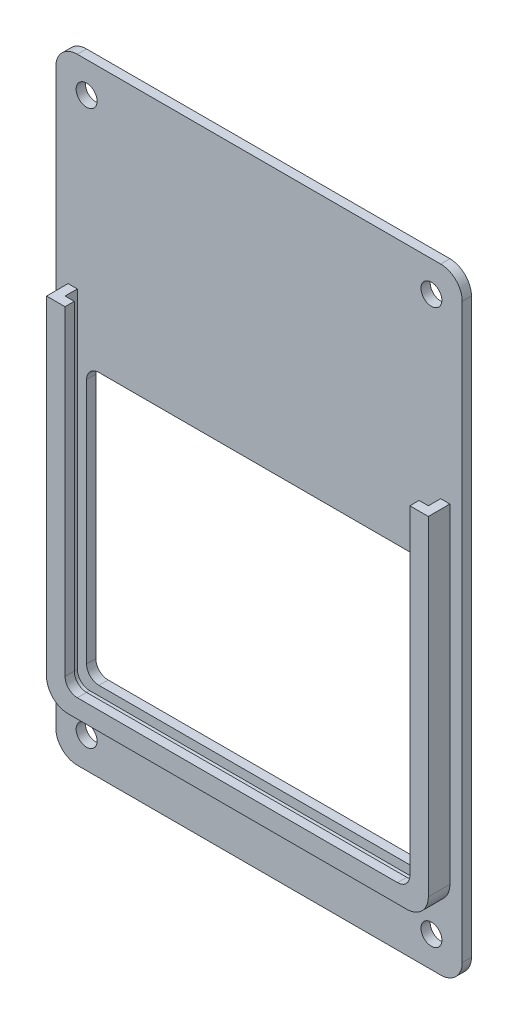
SolidWorks part; units mm, degrees
material "ABS"
ref_plane "Спереди" through (0, 0, 0) normal (0, 0, 1) x (1, 0, 0)
ref_plane "Сверху" through (0, 0, 0) normal (0, 1, 0) x (1, 0, 0)
ref_plane "Справа" through (0, 0, 0) normal (1, 0, 0) x (0, 0, -1)
sketch "Эскиз1" plane through (0, 0, 0) normal (0, 0, 1) x (1, 0, 0)
  line L1 (-33, -50) -> (33, -50)
  line L2 (-33, -50) -> (-33, 50)
  line L3 (-33, 50) -> (33, 50)
  line L4 (33, -50) -> (33, 50)
  line L5 (-33, -50) -> (33, 50) construction
  line L6 (-33, 50) -> (33, -50) construction
  point P0 (0, 0)
  dimension "D1" = 100
  dimension "D2" = 66
extrude "Бобышка-Вытянуть1" add sketch "Эскиз1" along normal blind 1.5 contours L2 L3 L4 L1
fillet "Скругление1" radius 3.5 4 edges at (-33, -50, 0.75) (33, -50, 0.75) (33, 50, 0.75) (-33, 50, 0.75)
sketch "Эскиз2" plane through (0, 0, 1.5) normal (0, 0, 1) x (1, 0, 0)
  line L0 (-29.5, -50) -> (29.5, -50) construction
  line L1 (-33, -50) -> (-24, -50)
  line L2 (-33, -50) -> (-33, -41)
  line L3 (-33, -41) -> (-24, -41)
  line L4 (-24, -50) -> (-24, -41)
  line L5 (33, -50) -> (24, -50)
  line L6 (33, -50) -> (33, -41)
  line L7 (33, -41) -> (24, -41)
  line L8 (24, -50) -> (24, -41)
  line L9 (-28, 7) -> (28, 7)
  line L10 (-28, 7) -> (-28, -37)
  line L11 (-28, -37) -> (28, -37)
  line L12 (28, 7) -> (28, -37)
  line L13 (-33, -46.5) -> (-33, 46.5) construction
  line L14 (33, -46.5) -> (33, 46.5) construction
  dimension "D1" = 57
  dimension "D2" = 5
  dimension "D3" = 5
  dimension "D4" = 13
  dimension "D5" = 9
extrude "Вырез-Вытянуть1" cut sketch "Эскиз2" against normal blind 1.5 contours L12 L9 L10 L3 L4 L11 L8 L7
fillet "Скругление2" radius 2 4 edges at (-28, -37, 0.75) (28, -37, 0.75) (-28, 7, 0.75) (28, 7, 0.75)
sketch "Эскиз3" plane through (0, 0, 1.5) normal (0, 0, 1) x (1, 0, 0)
  line L0 (-26, 7) -> (26, 7) construction
  line L1 (-28, -37) -> (28, -37)
  line L2 (-28, -37) -> (-28, 7)
  line L3 (-28, 7) -> (28, 7)
  line L4 (28, -37) -> (28, 7)
  line L5 (-29.5, -38.5) -> (29.5, -38.5)
  line L6 (-29.5, -38.5) -> (-29.5, 17)
  line L7 (-29.5, 17) -> (29.5, 17)
  line L8 (29.5, -38.5) -> (29.5, 17)
  line L10 (-26, -37) -> (26, -37) construction
  line L11 (28, 5) -> (28, -35) construction
  line L12 (-28, 5) -> (-28, -35) construction
  line L14 (-31, 17) -> (31, 17)
  line L15 (-31, 17) -> (-31, -40)
  line L16 (-31, -40) -> (31, -40)
  line L17 (31, 17) -> (31, -40)
  dimension "D1" = 1.5
  dimension "D2" = 1.5
  dimension "D3" = 1.5
  dimension "D4" = 10
  dimension "D5" = 1.5
  dimension "D6" = 1.5
  dimension "D7" = 1.5
extrude "Бобышка-Вытянуть2" add sketch "Эскиз3" along normal blind 2 contours L17 L14 L8 L5 L6 L15 L16
fillet "Скругление3" radius 2 2 edges at (29.5, -38.5, 2.5) (-29.5, -38.5, 2.5)
sketch "Эскиз4" plane through (0, 0, 3.5) normal (0, 0, 1) x (1, 0, 0)
  line L0 (-28, 5) -> (-28, -35) construction
  line L1 (-31, -40) -> (31, -40)
  line L2 (-31, -40) -> (-31, 17)
  line L3 (-31, 17) -> (31, 17)
  line L4 (31, -40) -> (31, 17)
  line L5 (-28, 17) -> (28, 17)
  line L6 (-28, 17) -> (-28, -37)
  line L7 (-28, -37) -> (28, -37)
  line L8 (28, 17) -> (28, -37)
  line L9 (-26, -37) -> (26, -37) construction
  line L10 (28, 5) -> (28, -35) construction
  line M4 (31, -40) -> (31, 17)
  line M5 (31, 17) -> (29.5, 17)
  line M6 (29.5, 17) -> (29.5, -36.5)
  arc M7 (29.5, -36.5) -> (27.5, -38.5) centre (27.5, -36.5) cw
  line M8 (27.5, -38.5) -> (-27.5, -38.5)
  arc M9 (-27.5, -38.5) -> (-29.5, -36.5) centre (-27.5, -36.5) cw
  line M10 (-29.5, -36.5) -> (-29.5, 17)
  line M11 (-29.5, 17) -> (-31, 17)
  line M12 (-31, 17) -> (-31, -40)
  line M13 (-31, -40) -> (31, -40)
extrude "Бобышка-Вытянуть3" add sketch "Эскиз4" along normal blind 1.5 contours M13 M4 M5 M6 M7 M8 M9 M10 M11 M12 | L3 L8 L7 L6 M10 M9 M8 M7 M6
fillet "Скругление4" radius 2 2 edges at (-28, -37, 4.25) (28, -37, 4.25)
fillet "Скругление5" radius 3.5 2 edges at (-31, -40, 3.25) (31, -40, 3.25)
sketch "Эскиз5" plane through (0, 0, 0) normal (0, 0, -1) x (-1, 0, 0)
  line L1 (-24, -38.5) -> (24, -38.5)
  line L2 (-24, -38.5) -> (-24, -48.5)
  line L3 (-24, -48.5) -> (24, -48.5)
  line L4 (24, -38.5) -> (24, -48.5)
  line L5 (-31.5, 48.5) -> (31.5, 48.5)
  line L6 (-31.5, 48.5) -> (-31.5, 8)
  line L7 (-31.5, 8) -> (31.5, 8)
  line L8 (31.5, 48.5) -> (31.5, 8)
  line L9 (31.5, 48.5) -> (24, 48.5)
  line L10 (31.5, 48.5) -> (31.5, 41)
  line L11 (31.5, 41) -> (24, 41)
  line L12 (24, 48.5) -> (24, 41)
  line L13 (-31.5, 48.5) -> (-24, 48.5)
  line L14 (-31.5, 48.5) -> (-31.5, 41)
  line L15 (-31.5, 41) -> (-24, 41)
  line L16 (-24, 48.5) -> (-24, 41)
  line L18 (-33, -46.5) -> (-33, 46.5) construction
  line L19 (29.5, 50) -> (-29.5, 50) construction
  line L20 (29.5, -50) -> (-29.5, -50) construction
  dimension "D1" = 7.5
  dimension "D2" = 40.5
  dimension "D3" = 63
  dimension "D4" = 1.5
  dimension "D5" = 1.5
  dimension "D6" = 10
  dimension "D7" = 48
  dimension "D8" = 1.5
  dimension "D9" = 9
extrude "Бобышка-Вытянуть4" add sketch "Эскиз5" along normal blind 1.5 contours L5 L16 L15 L6 L7 L8 L11 L12 | L4 L1 L2 L3
fillet "Скругление6" radius 2 12 edges at (24, 41, -0.75) (24, 48.5, -0.75) (31.5, 41, -0.75) (31.5, 8, -0.75) (-31.5, 8, -0.75) (-31.5, 41, -0.75) (-24, 41, -0.75) (-24, 48.5, -0.75) (-24, -48.5, -0.75) (-24, -38.5, -0.75) (24, -38.5, -0.75) (24, -48.5, -0.75)
sketch "Эскиз6" plane through (0, 0, 1.5) normal (0, 0, 1) x (1, 0, 0)
  line L1 (-29.5, 50) -> (29.5, 50) construction
  line L2 (-33, -46.5) -> (-33, 46.5) construction
  line L3 (33, -46.5) -> (33, 46.5) construction
  line L4 (-29.5, -50) -> (29.5, -50) construction
  point P0 (-28, 45)
  point P1 (28, 45)
  point P3 (-28, -45)
  point P4 (28, -45)
  dimension "D1" = 5
  dimension "D2" = 5
  dimension "D3" = 5
  dimension "D4" = 5
hole_wizard "Отверстие с зазором M31" positions "Эскиз7" profile "Эскиз8" hole size "M3" standard "DIN" end condition through all
sketch "Эскиз7" plane through (0, 0, 1.5) normal (0, 0, 1) x (1, 0, 0)
  point P0 (-28, 45)
  point P3 (28, 45)
  point P6 (28, -45)
  point P9 (-28, -45)
sketch "Эскиз8" plane through (-28, 45, 1.5) normal (1, 0, 0) x (0, -1, 0)
  line L0 (0, 0) -> (0, 3)
  line L1 (0, 3) -> (1.7, 3)
  line L2 (1.7, 3) -> (1.7, 0)
  line L5 (1.7, 0) -> (0, 0)
  line L11 (0, -6.35) -> (0, 107.95) construction
  dimension "Диаметр сквозного отверстия" = 3.4
  dimension "Глубина сквозного отверстия" = 3
sketch3d "Трехмерный эскиз1"
  line L0 (-22.5, 43, -1.5) -> (-22.5, 46.5, -1.5)
  line L1 (-22, 47, -1.5) -> (22, 47, -1.5)
  line L2 (22.5, 46.5, -1.5) -> (22.5, 43, -1.5)
  line L3 (26, 39.5, -1.5) -> (29.5, 39.5, -1.5)
  line L4 (30, 39, -1.5) -> (30, 10, -1.5)
  line L5 (29.5, 9.5, -1.5) -> (-29.5, 9.5, -1.5)
  line L6 (-30, 10, -1.5) -> (-30, 39, -1.5)
  line L7 (-29.5, 39.5, -1.5) -> (-26, 39.5, -1.5)
  line L8 (-22.5, 43, -1.5) -> (-22.5, 46.5, -1.5)
  line L9 (-22, 47, -1.5) -> (22, 47, -1.5)
  line L10 (22.5, 46.5, -1.5) -> (22.5, 43, -1.5)
  line L11 (26, 39.5, -1.5) -> (29.5, 39.5, -1.5)
  line L12 (30, 39, -1.5) -> (30, 10, -1.5)
  line L13 (29.5, 9.5, -1.5) -> (-29.5, 9.5, -1.5)
  line L14 (-30, 10, -1.5) -> (-30, 39, -1.5)
  line L15 (-29.5, 39.5, -1.5) -> (-26, 39.5, -1.5)
  spline S0 degree 5 poles (-1959.1652, 518.9756, -1.5) (-791.4073, 54.891, -1.5) (-209.3847, 47.0734, -1.5) (-18.9678, 44.5568, -1.5) (-22.5874, 45.5883, -1.5) (-22.4979, 46.5524, -1.5) (-22.4964, 46.564, -1.5) (-22.4917, 46.5929, -1.5) (-22.4853, 46.6214, -1.5) (-22.4808, 46.6383, -1.5) (-22.4704, 46.6717, -1.5) (-22.457, 46.7041, -1.5) (-22.4496, 46.7199, -1.5) (-22.4333, 46.751, -1.5) (-22.4144, 46.7805, -1.5) (-22.4044, 46.7948, -1.5) (-22.383, 46.8226, -1.5) (-22.3593, 46.8484, -1.5) (-22.3469, 46.8608, -1.5) (-22.321, 46.8844, -1.5) (-22.2931, 46.9056, -1.5) (-22.2788, 46.9156, -1.5) (-22.2492, 46.9344, -1.5) (-22.218, 46.9505, -1.5) (-22.2021, 46.9579, -1.5) (-22.1699, 46.9711, -1.5) (-22.1366, 46.9813, -1.5) (-22.1198, 46.9857, -1.5) (-22.0915, 46.9919, -1.5) (-22.0629, 46.9965, -1.5) (-22.0514, 46.998, -1.5) (-21.0953, 47.085, -1.5) (-20.0736, 43.5304, -1.5) (-22.5419, 233.6284, -1.5) (-34.0122, 814.5009, -1.5) (432.7664, 1987.0289, -1.5) knots -6.044252 -6.044252 -6.044252 -6.044252 -6.044252 -6.044252 0.037136 0.037136 0.037136 0.111408 0.111408 0.111408 0.222815 0.222815 0.222815 0.334223 0.334223 0.334223 0.445631 0.445631 0.445631 0.557039 0.557039 0.557039 0.668446 0.668446 0.668446 0.779854 0.779854 0.779854 0.890372 0.890372 0.890372 0.963754 0.963754 0.963754 6.995146 6.995146 6.995146 6.995146 6.995146 6.995146 only from (-22.5, 46.5, -1.5) to (-22, 47, -1.5)
  spline S1 degree 5 poles (494.4847, 1983.6668, -1.5) (30.3909, 815.9073, -1.5) (22.5734, 233.8847, -1.5) (20.0568, 43.4678, -1.5) (21.0883, 47.0874, -1.5) (22.0524, 46.9979, -1.5) (22.064, 46.9964, -1.5) (22.0929, 46.9917, -1.5) (22.1214, 46.9853, -1.5) (22.1383, 46.9808, -1.5) (22.1717, 46.9704, -1.5) (22.2041, 46.957, -1.5) (22.2199, 46.9496, -1.5) (22.251, 46.9333, -1.5) (22.2805, 46.9144, -1.5) (22.2948, 46.9044, -1.5) (22.3226, 46.883, -1.5) (22.3484, 46.8593, -1.5) (22.3608, 46.8469, -1.5) (22.3844, 46.821, -1.5) (22.4056, 46.7931, -1.5) (22.4156, 46.7788, -1.5) (22.4344, 46.7492, -1.5) (22.4505, 46.718, -1.5) (22.4579, 46.7021, -1.5) (22.4711, 46.6699, -1.5) (22.4813, 46.6366, -1.5) (22.4857, 46.6198, -1.5) (22.4919, 46.5915, -1.5) (22.4965, 46.5629, -1.5) (22.498, 46.5514, -1.5) (22.585, 45.5953, -1.5) (19.0304, 44.5736, -1.5) (209.1284, 47.0419, -1.5) (790.0009, 58.5122, -1.5) (1962.5397, -408.252, -1.4999) knots -6.044252 -6.044252 -6.044252 -6.044252 -6.044252 -6.044252 0.037136 0.037136 0.037136 0.111408 0.111408 0.111408 0.222815 0.222815 0.222815 0.334223 0.334223 0.334223 0.445631 0.445631 0.445631 0.557039 0.557039 0.557039 0.668446 0.668446 0.668446 0.779854 0.779854 0.779854 0.890372 0.890372 0.890372 0.963754 0.963754 0.963754 6.995146 6.995146 6.995146 6.995146 6.995146 6.995146 only from (22, 47, -1.5) to (22.5, 46.5, -1.5)
  spline S2 degree 5 poles (-1977.3234, 23.7298, -1.5) (-763.4699, 42.68, -1.5) (-163.6031, 50.047, -1.5) (29.3183, 50.0118, -1.5) (22.1783, 46.2545, -1.5) (22.5145, 42.6332, -1.5) (22.5252, 42.552, -1.5) (22.5582, 42.3497, -1.5) (22.6028, 42.1502, -1.5) (22.6342, 42.0318, -1.5) (22.7069, 41.798, -1.5) (22.8009, 41.5716, -1.5) (22.853, 41.4605, -1.5) (22.9668, 41.2431, -1.5) (23.0989, 41.0364, -1.5) (23.1694, 40.9361, -1.5) (23.3189, 40.7418, -1.5) (23.485, 40.5613, -1.5) (23.5719, 40.4747, -1.5) (23.7531, 40.3095, -1.5) (23.948, 40.1607, -1.5) (24.0487, 40.0907, -1.5) (24.2558, 39.9594, -1.5) (24.4737, 39.8465, -1.5) (24.585, 39.7949, -1.5) (24.811, 39.7022, -1.5) (25.0441, 39.6307, -1.5) (25.1617, 39.6001, -1.5) (25.3594, 39.5565, -1.5) (25.5598, 39.5243, -1.5) (25.6401, 39.514, -1.5) (29.2335, 39.1869, -1.5) (32.9591, 46.2077, -1.5) (33.0043, -146.8371, -1.5) (25.7256, -746.7213, -1.5) (7.8554, -1960.3791, -1.5) knots -3.19175 -3.19175 -3.19175 -3.19175 -3.19175 -3.19175 0.037136 0.037136 0.037136 0.111408 0.111408 0.111408 0.222815 0.222815 0.222815 0.334223 0.334223 0.334223 0.445631 0.445631 0.445631 0.557039 0.557039 0.557039 0.668446 0.668446 0.668446 0.779854 0.779854 0.779854 0.890372 0.890372 0.890372 0.963754 0.963754 0.963754 4.167936 4.167936 4.167936 4.167936 4.167936 4.167936 only from (22.5, 43, -1.5) to (26, 39.5, -1.5)
  spline S3 degree 5 poles (501.984, 1976.1663, -1.5) (37.8909, 808.4073, -1.5) (30.0734, 226.3847, -1.5) (27.5568, 35.9678, -1.5) (28.5883, 39.5874, -1.5) (29.5524, 39.4979, -1.5) (29.564, 39.4964, -1.5) (29.5929, 39.4917, -1.5) (29.6214, 39.4853, -1.5) (29.6383, 39.4808, -1.5) (29.6717, 39.4704, -1.5) (29.7041, 39.457, -1.5) (29.7199, 39.4496, -1.5) (29.751, 39.4333, -1.5) (29.7805, 39.4144, -1.5) (29.7948, 39.4044, -1.5) (29.8226, 39.383, -1.5) (29.8484, 39.3593, -1.5) (29.8608, 39.3469, -1.5) (29.8844, 39.321, -1.5) (29.9056, 39.2931, -1.5) (29.9156, 39.2788, -1.5) (29.9344, 39.2492, -1.5) (29.9505, 39.218, -1.5) (29.9579, 39.2021, -1.5) (29.9711, 39.1699, -1.5) (29.9813, 39.1366, -1.5) (29.9857, 39.1198, -1.5) (29.9919, 39.0915, -1.5) (29.9965, 39.0629, -1.5) (29.998, 39.0514, -1.5) (30.085, 38.0953, -1.5) (26.5304, 37.0736, -1.5) (216.6284, 39.5419, -1.5) (797.5009, 51.0122, -1.5) (1970.0403, -415.7606, -1.5) knots -6.044252 -6.044252 -6.044252 -6.044252 -6.044252 -6.044252 0.037136 0.037136 0.037136 0.111408 0.111408 0.111408 0.222815 0.222815 0.222815 0.334223 0.334223 0.334223 0.445631 0.445631 0.445631 0.557039 0.557039 0.557039 0.668446 0.668446 0.668446 0.779854 0.779854 0.779854 0.890372 0.890372 0.890372 0.963754 0.963754 0.963754 6.995146 6.995146 6.995146 6.995146 6.995146 6.995146 only from (29.5, 39.5, -1.5) to (30, 39, -1.5)
  spline S4 degree 5 poles (1966.6644, -462.4869, -1.5) (798.9073, 1.6091, -1.5) (216.8847, 9.4266, -1.5) (26.4678, 11.9432, -1.5) (30.0874, 10.9117, -1.5) (29.9979, 9.9476, -1.5) (29.9964, 9.936, -1.5) (29.9917, 9.9071, -1.5) (29.9853, 9.8786, -1.5) (29.9808, 9.8617, -1.5) (29.9704, 9.8283, -1.5) (29.957, 9.7959, -1.5) (29.9496, 9.7801, -1.5) (29.9333, 9.749, -1.5) (29.9144, 9.7195, -1.5) (29.9044, 9.7052, -1.5) (29.883, 9.6774, -1.5) (29.8593, 9.6516, -1.5) (29.8469, 9.6392, -1.5) (29.821, 9.6156, -1.5) (29.7931, 9.5944, -1.5) (29.7788, 9.5844, -1.5) (29.7492, 9.5656, -1.5) (29.718, 9.5495, -1.5) (29.7021, 9.5421, -1.5) (29.6699, 9.5289, -1.5) (29.6366, 9.5187, -1.5) (29.6198, 9.5143, -1.5) (29.5915, 9.5081, -1.5) (29.5629, 9.5035, -1.5) (29.5514, 9.502, -1.5) (28.5953, 9.415, -1.5) (27.5736, 12.9696, -1.5) (30.0419, -177.1284, -1.5) (41.5122, -758.0009, -1.5) (-425.2662, -1930.5375, -1.5) knots -6.044252 -6.044252 -6.044252 -6.044252 -6.044252 -6.044252 0.037136 0.037136 0.037136 0.111408 0.111408 0.111408 0.222815 0.222815 0.222815 0.334223 0.334223 0.334223 0.445631 0.445631 0.445631 0.557039 0.557039 0.557039 0.668446 0.668446 0.668446 0.779854 0.779854 0.779854 0.890372 0.890372 0.890372 0.963754 0.963754 0.963754 6.995146 6.995146 6.995146 6.995146 6.995146 6.995146 only from (30, 10, -1.5) to (29.5, 9.5, -1.5)
  spline S5 degree 5 poles (-501.9891, -1927.1637, -1.5) (-37.8909, -759.4073, -1.5) (-30.0734, -177.3847, -1.5) (-27.5568, 13.0322, -1.5) (-28.5883, 9.4126, -1.5) (-29.5524, 9.5021, -1.5) (-29.564, 9.5036, -1.5) (-29.5929, 9.5083, -1.5) (-29.6214, 9.5147, -1.5) (-29.6383, 9.5192, -1.5) (-29.6717, 9.5296, -1.5) (-29.7041, 9.543, -1.5) (-29.7199, 9.5504, -1.5) (-29.751, 9.5667, -1.5) (-29.7805, 9.5856, -1.5) (-29.7948, 9.5956, -1.5) (-29.8226, 9.617, -1.5) (-29.8484, 9.6407, -1.5) (-29.8608, 9.6531, -1.5) (-29.8844, 9.679, -1.5) (-29.9056, 9.7069, -1.5) (-29.9156, 9.7212, -1.5) (-29.9344, 9.7508, -1.5) (-29.9505, 9.782, -1.5) (-29.9579, 9.7979, -1.5) (-29.9711, 9.8301, -1.5) (-29.9813, 9.8634, -1.5) (-29.9857, 9.8802, -1.5) (-29.9919, 9.9085, -1.5) (-29.9965, 9.9371, -1.5) (-29.998, 9.9486, -1.5) (-30.085, 10.9047, -1.5) (-26.5304, 11.9264, -1.5) (-216.6284, 9.4581, -1.5) (-797.5009, -2.0123, -1.5) (-1970.043, 464.7742, -1.5) knots -6.044252 -6.044252 -6.044252 -6.044252 -6.044252 -6.044252 0.037136 0.037136 0.037136 0.111408 0.111408 0.111408 0.222815 0.222815 0.222815 0.334223 0.334223 0.334223 0.445631 0.445631 0.445631 0.557039 0.557039 0.557039 0.668446 0.668446 0.668446 0.779854 0.779854 0.779854 0.890372 0.890372 0.890372 0.963754 0.963754 0.963754 6.995146 6.995146 6.995146 6.995146 6.995146 6.995146 only from (-29.5, 9.5, -1.5) to (-30, 10, -1.5)
  spline S6 degree 5 poles (-1966.6635, 511.5027, -1.5) (-798.9073, 47.3909, -1.5) (-216.8847, 39.5734, -1.5) (-26.4678, 37.0568, -1.5) (-30.0874, 38.0883, -1.5) (-29.9979, 39.0524, -1.5) (-29.9964, 39.064, -1.5) (-29.9917, 39.0929, -1.5) (-29.9853, 39.1214, -1.5) (-29.9808, 39.1383, -1.5) (-29.9704, 39.1717, -1.5) (-29.957, 39.2041, -1.5) (-29.9496, 39.2199, -1.5) (-29.9333, 39.251, -1.5) (-29.9144, 39.2805, -1.5) (-29.9044, 39.2948, -1.5) (-29.883, 39.3226, -1.5) (-29.8593, 39.3484, -1.5) (-29.8469, 39.3608, -1.5) (-29.821, 39.3844, -1.5) (-29.7931, 39.4056, -1.5) (-29.7788, 39.4156, -1.5) (-29.7492, 39.4344, -1.5) (-29.718, 39.4505, -1.5) (-29.7021, 39.4579, -1.5) (-29.6699, 39.4711, -1.5) (-29.6366, 39.4813, -1.5) (-29.6198, 39.4857, -1.5) (-29.5915, 39.4919, -1.5) (-29.5629, 39.4965, -1.5) (-29.5514, 39.498, -1.5) (-28.5953, 39.585, -1.5) (-27.5736, 36.0304, -1.5) (-30.0419, 226.1284, -1.5) (-41.5122, 807.0009, -1.5) (425.2707, 1979.5276, -1.5) knots -6.044252 -6.044252 -6.044252 -6.044252 -6.044252 -6.044252 0.037136 0.037136 0.037136 0.111408 0.111408 0.111408 0.222815 0.222815 0.222815 0.334223 0.334223 0.334223 0.445631 0.445631 0.445631 0.557039 0.557039 0.557039 0.668446 0.668446 0.668446 0.779854 0.779854 0.779854 0.890372 0.890372 0.890372 0.963754 0.963754 0.963754 6.995146 6.995146 6.995146 6.995146 6.995146 6.995146 only from (-30, 39, -1.5) to (-29.5, 39.5, -1.5)
  spline S7 degree 5 poles (-6.7304, -1960.3231, -1.5) (-25.68, -746.4699, -1.5) (-33.047, -146.6031, -1.5) (-33.0118, 46.3183, -1.5) (-29.2545, 39.1783, -1.5) (-25.6332, 39.5145, -1.5) (-25.552, 39.5252, -1.5) (-25.3497, 39.5582, -1.5) (-25.1502, 39.6028, -1.5) (-25.0318, 39.6342, -1.5) (-24.798, 39.7069, -1.5) (-24.5716, 39.8009, -1.5) (-24.4605, 39.853, -1.5) (-24.2431, 39.9668, -1.5) (-24.0364, 40.0989, -1.5) (-23.9361, 40.1694, -1.5) (-23.7418, 40.3189, -1.5) (-23.5613, 40.485, -1.5) (-23.4747, 40.5719, -1.5) (-23.3095, 40.7531, -1.5) (-23.1607, 40.948, -1.5) (-23.0907, 41.0487, -1.5) (-22.9594, 41.2558, -1.5) (-22.8465, 41.4737, -1.5) (-22.7949, 41.585, -1.5) (-22.7022, 41.811, -1.5) (-22.6307, 42.0441, -1.5) (-22.6001, 42.1617, -1.5) (-22.5565, 42.3594, -1.5) (-22.5243, 42.5598, -1.5) (-22.514, 42.6401, -1.5) (-22.1869, 46.2335, -1.5) (-29.2077, 49.9591, -1.5) (163.8371, 50.0043, -1.5) (763.7213, 42.7256, -1.5) (1977.3792, 24.8548, -1.5) knots -3.19175 -3.19175 -3.19175 -3.19175 -3.19175 -3.19175 0.037136 0.037136 0.037136 0.111408 0.111408 0.111408 0.222815 0.222815 0.222815 0.334223 0.334223 0.334223 0.445631 0.445631 0.445631 0.557039 0.557039 0.557039 0.668446 0.668446 0.668446 0.779854 0.779854 0.779854 0.890372 0.890372 0.890372 0.963754 0.963754 0.963754 4.167936 4.167936 4.167936 4.167936 4.167936 4.167936 only from (-26, 39.5, -1.5) to (-22.5, 43, -1.5)
  spline S8 degree 5 poles (-22.5, 46.5, -1.5) (-22.5, 46.5058, -1.5) (-22.5, 46.5117, -1.5) (-22.5, 46.5175, -1.5) (-22.4996, 46.5349, -1.5) (-22.4979, 46.5524, -1.5) (-22.4964, 46.564, -1.5) (-22.4917, 46.5929, -1.5) (-22.4853, 46.6214, -1.5) (-22.4808, 46.6383, -1.5) (-22.4704, 46.6717, -1.5) (-22.457, 46.7041, -1.5) (-22.4496, 46.7199, -1.5) (-22.4333, 46.751, -1.5) (-22.4144, 46.7805, -1.5) (-22.4044, 46.7948, -1.5) (-22.383, 46.8226, -1.5) (-22.3593, 46.8484, -1.5) (-22.3469, 46.8608, -1.5) (-22.321, 46.8844, -1.5) (-22.2931, 46.9056, -1.5) (-22.2788, 46.9156, -1.5) (-22.2492, 46.9344, -1.5) (-22.218, 46.9505, -1.5) (-22.2021, 46.9579, -1.5) (-22.1699, 46.9711, -1.5) (-22.1366, 46.9813, -1.5) (-22.1198, 46.9857, -1.5) (-22.0915, 46.9919, -1.5) (-22.0629, 46.9965, -1.5) (-22.0514, 46.998, -1.5) (-22.0342, 46.9996, -1.5) (-22.0171, 47, -1.5) (-22.0114, 47, -1.5) (-22.0057, 47, -1.5) (-22, 47, -1.5) knots 0 0 0 0 0 0 0.037136 0.037136 0.037136 0.111408 0.111408 0.111408 0.222815 0.222815 0.222815 0.334223 0.334223 0.334223 0.445631 0.445631 0.445631 0.557039 0.557039 0.557039 0.668446 0.668446 0.668446 0.779854 0.779854 0.779854 0.890372 0.890372 0.890372 0.963754 0.963754 0.963754 1 1 1 1 1 1
  spline S9 degree 5 poles (22, 47, -1.5) (22.0058, 47, -1.5) (22.0117, 47, -1.5) (22.0175, 47, -1.5) (22.0349, 46.9996, -1.5) (22.0524, 46.9979, -1.5) (22.064, 46.9964, -1.5) (22.0929, 46.9917, -1.5) (22.1214, 46.9853, -1.5) (22.1383, 46.9808, -1.5) (22.1717, 46.9704, -1.5) (22.2041, 46.957, -1.5) (22.2199, 46.9496, -1.5) (22.251, 46.9333, -1.5) (22.2805, 46.9144, -1.5) (22.2948, 46.9044, -1.5) (22.3226, 46.883, -1.5) (22.3484, 46.8593, -1.5) (22.3608, 46.8469, -1.5) (22.3844, 46.821, -1.5) (22.4056, 46.7931, -1.5) (22.4156, 46.7788, -1.5) (22.4344, 46.7492, -1.5) (22.4505, 46.718, -1.5) (22.4579, 46.7021, -1.5) (22.4711, 46.6699, -1.5) (22.4813, 46.6366, -1.5) (22.4857, 46.6198, -1.5) (22.4919, 46.5915, -1.5) (22.4965, 46.5629, -1.5) (22.498, 46.5514, -1.5) (22.4996, 46.5342, -1.5) (22.5, 46.5171, -1.5) (22.5, 46.5114, -1.5) (22.5, 46.5057, -1.5) (22.5, 46.5, -1.5) knots 0 0 0 0 0 0 0.037136 0.037136 0.037136 0.111408 0.111408 0.111408 0.222815 0.222815 0.222815 0.334223 0.334223 0.334223 0.445631 0.445631 0.445631 0.557039 0.557039 0.557039 0.668446 0.668446 0.668446 0.779854 0.779854 0.779854 0.890372 0.890372 0.890372 0.963754 0.963754 0.963754 1 1 1 1 1 1
  spline S10 degree 5 poles (22.5, 43, -1.5) (22.5, 42.9592, -1.5) (22.5, 42.9184, -1.5) (22.5003, 42.8777, -1.5) (22.5031, 42.7554, -1.5) (22.5145, 42.6332, -1.5) (22.5252, 42.552, -1.5) (22.5582, 42.3497, -1.5) (22.6028, 42.1502, -1.5) (22.6342, 42.0318, -1.5) (22.7069, 41.798, -1.5) (22.8009, 41.5716, -1.5) (22.853, 41.4605, -1.5) (22.9668, 41.2431, -1.5) (23.0989, 41.0364, -1.5) (23.1694, 40.9361, -1.5) (23.3189, 40.7418, -1.5) (23.485, 40.5613, -1.5) (23.5719, 40.4747, -1.5) (23.7531, 40.3095, -1.5) (23.948, 40.1607, -1.5) (24.0487, 40.0907, -1.5) (24.2558, 39.9594, -1.5) (24.4737, 39.8465, -1.5) (24.585, 39.7949, -1.5) (24.811, 39.7022, -1.5) (25.0441, 39.6307, -1.5) (25.1617, 39.6001, -1.5) (25.3594, 39.5565, -1.5) (25.5598, 39.5243, -1.5) (25.6401, 39.514, -1.5) (25.7603, 39.503, -1.5) (25.8806, 39.5003, -1.5) (25.9204, 39.5, -1.5) (25.9602, 39.5, -1.5) (26, 39.5, -1.5) knots 0 0 0 0 0 0 0.037136 0.037136 0.037136 0.111408 0.111408 0.111408 0.222815 0.222815 0.222815 0.334223 0.334223 0.334223 0.445631 0.445631 0.445631 0.557039 0.557039 0.557039 0.668446 0.668446 0.668446 0.779854 0.779854 0.779854 0.890372 0.890372 0.890372 0.963754 0.963754 0.963754 1 1 1 1 1 1
  spline S11 degree 5 poles (29.5, 39.5, -1.5) (29.5058, 39.5, -1.5) (29.5117, 39.5, -1.5) (29.5175, 39.5, -1.5) (29.5349, 39.4996, -1.5) (29.5524, 39.4979, -1.5) (29.564, 39.4964, -1.5) (29.5929, 39.4917, -1.5) (29.6214, 39.4853, -1.5) (29.6383, 39.4808, -1.5) (29.6717, 39.4704, -1.5) (29.7041, 39.457, -1.5) (29.7199, 39.4496, -1.5) (29.751, 39.4333, -1.5) (29.7805, 39.4144, -1.5) (29.7948, 39.4044, -1.5) (29.8226, 39.383, -1.5) (29.8484, 39.3593, -1.5) (29.8608, 39.3469, -1.5) (29.8844, 39.321, -1.5) (29.9056, 39.2931, -1.5) (29.9156, 39.2788, -1.5) (29.9344, 39.2492, -1.5) (29.9505, 39.218, -1.5) (29.9579, 39.2021, -1.5) (29.9711, 39.1699, -1.5) (29.9813, 39.1366, -1.5) (29.9857, 39.1198, -1.5) (29.9919, 39.0915, -1.5) (29.9965, 39.0629, -1.5) (29.998, 39.0514, -1.5) (29.9996, 39.0342, -1.5) (30, 39.0171, -1.5) (30, 39.0114, -1.5) (30, 39.0057, -1.5) (30, 39, -1.5) knots 0 0 0 0 0 0 0.037136 0.037136 0.037136 0.111408 0.111408 0.111408 0.222815 0.222815 0.222815 0.334223 0.334223 0.334223 0.445631 0.445631 0.445631 0.557039 0.557039 0.557039 0.668446 0.668446 0.668446 0.779854 0.779854 0.779854 0.890372 0.890372 0.890372 0.963754 0.963754 0.963754 1 1 1 1 1 1
  spline S12 degree 5 poles (30, 10, -1.5) (30, 9.9942, -1.5) (30, 9.9883, -1.5) (30, 9.9825, -1.5) (29.9996, 9.9651, -1.5) (29.9979, 9.9476, -1.5) (29.9964, 9.936, -1.5) (29.9917, 9.9071, -1.5) (29.9853, 9.8786, -1.5) (29.9808, 9.8617, -1.5) (29.9704, 9.8283, -1.5) (29.957, 9.7959, -1.5) (29.9496, 9.7801, -1.5) (29.9333, 9.749, -1.5) (29.9144, 9.7195, -1.5) (29.9044, 9.7052, -1.5) (29.883, 9.6774, -1.5) (29.8593, 9.6516, -1.5) (29.8469, 9.6392, -1.5) (29.821, 9.6156, -1.5) (29.7931, 9.5944, -1.5) (29.7788, 9.5844, -1.5) (29.7492, 9.5656, -1.5) (29.718, 9.5495, -1.5) (29.7021, 9.5421, -1.5) (29.6699, 9.5289, -1.5) (29.6366, 9.5187, -1.5) (29.6198, 9.5143, -1.5) (29.5915, 9.5081, -1.5) (29.5629, 9.5035, -1.5) (29.5514, 9.502, -1.5) (29.5342, 9.5004, -1.5) (29.5171, 9.5, -1.5) (29.5114, 9.5, -1.5) (29.5057, 9.5, -1.5) (29.5, 9.5, -1.5) knots 0 0 0 0 0 0 0.037136 0.037136 0.037136 0.111408 0.111408 0.111408 0.222815 0.222815 0.222815 0.334223 0.334223 0.334223 0.445631 0.445631 0.445631 0.557039 0.557039 0.557039 0.668446 0.668446 0.668446 0.779854 0.779854 0.779854 0.890372 0.890372 0.890372 0.963754 0.963754 0.963754 1 1 1 1 1 1
  spline S13 degree 5 poles (-29.5, 9.5, -1.5) (-29.5058, 9.5, -1.5) (-29.5117, 9.5, -1.5) (-29.5175, 9.5, -1.5) (-29.5349, 9.5004, -1.5) (-29.5524, 9.5021, -1.5) (-29.564, 9.5036, -1.5) (-29.5929, 9.5083, -1.5) (-29.6214, 9.5147, -1.5) (-29.6383, 9.5192, -1.5) (-29.6717, 9.5296, -1.5) (-29.7041, 9.543, -1.5) (-29.7199, 9.5504, -1.5) (-29.751, 9.5667, -1.5) (-29.7805, 9.5856, -1.5) (-29.7948, 9.5956, -1.5) (-29.8226, 9.617, -1.5) (-29.8484, 9.6407, -1.5) (-29.8608, 9.6531, -1.5) (-29.8844, 9.679, -1.5) (-29.9056, 9.7069, -1.5) (-29.9156, 9.7212, -1.5) (-29.9344, 9.7508, -1.5) (-29.9505, 9.782, -1.5) (-29.9579, 9.7979, -1.5) (-29.9711, 9.8301, -1.5) (-29.9813, 9.8634, -1.5) (-29.9857, 9.8802, -1.5) (-29.9919, 9.9085, -1.5) (-29.9965, 9.9371, -1.5) (-29.998, 9.9486, -1.5) (-29.9996, 9.9658, -1.5) (-30, 9.9829, -1.5) (-30, 9.9886, -1.5) (-30, 9.9943, -1.5) (-30, 10, -1.5) knots 0 0 0 0 0 0 0.037136 0.037136 0.037136 0.111408 0.111408 0.111408 0.222815 0.222815 0.222815 0.334223 0.334223 0.334223 0.445631 0.445631 0.445631 0.557039 0.557039 0.557039 0.668446 0.668446 0.668446 0.779854 0.779854 0.779854 0.890372 0.890372 0.890372 0.963754 0.963754 0.963754 1 1 1 1 1 1
  spline S14 degree 5 poles (-30, 39, -1.5) (-30, 39.0058, -1.5) (-30, 39.0117, -1.5) (-30, 39.0175, -1.5) (-29.9996, 39.0349, -1.5) (-29.9979, 39.0524, -1.5) (-29.9964, 39.064, -1.5) (-29.9917, 39.0929, -1.5) (-29.9853, 39.1214, -1.5) (-29.9808, 39.1383, -1.5) (-29.9704, 39.1717, -1.5) (-29.957, 39.2041, -1.5) (-29.9496, 39.2199, -1.5) (-29.9333, 39.251, -1.5) (-29.9144, 39.2805, -1.5) (-29.9044, 39.2948, -1.5) (-29.883, 39.3226, -1.5) (-29.8593, 39.3484, -1.5) (-29.8469, 39.3608, -1.5) (-29.821, 39.3844, -1.5) (-29.7931, 39.4056, -1.5) (-29.7788, 39.4156, -1.5) (-29.7492, 39.4344, -1.5) (-29.718, 39.4505, -1.5) (-29.7021, 39.4579, -1.5) (-29.6699, 39.4711, -1.5) (-29.6366, 39.4813, -1.5) (-29.6198, 39.4857, -1.5) (-29.5915, 39.4919, -1.5) (-29.5629, 39.4965, -1.5) (-29.5514, 39.498, -1.5) (-29.5342, 39.4996, -1.5) (-29.5171, 39.5, -1.5) (-29.5114, 39.5, -1.5) (-29.5057, 39.5, -1.5) (-29.5, 39.5, -1.5) knots 0 0 0 0 0 0 0.037136 0.037136 0.037136 0.111408 0.111408 0.111408 0.222815 0.222815 0.222815 0.334223 0.334223 0.334223 0.445631 0.445631 0.445631 0.557039 0.557039 0.557039 0.668446 0.668446 0.668446 0.779854 0.779854 0.779854 0.890372 0.890372 0.890372 0.963754 0.963754 0.963754 1 1 1 1 1 1
  spline S15 degree 5 poles (-26, 39.5, -1.5) (-25.9592, 39.5, -1.5) (-25.9184, 39.5, -1.5) (-25.8777, 39.5003, -1.5) (-25.7554, 39.5031, -1.5) (-25.6332, 39.5145, -1.5) (-25.552, 39.5252, -1.5) (-25.3497, 39.5582, -1.5) (-25.1502, 39.6028, -1.5) (-25.0318, 39.6342, -1.5) (-24.798, 39.7069, -1.5) (-24.5716, 39.8009, -1.5) (-24.4605, 39.853, -1.5) (-24.2431, 39.9668, -1.5) (-24.0364, 40.0989, -1.5) (-23.9361, 40.1694, -1.5) (-23.7418, 40.3189, -1.5) (-23.5613, 40.485, -1.5) (-23.4747, 40.5719, -1.5) (-23.3095, 40.7531, -1.5) (-23.1607, 40.948, -1.5) (-23.0907, 41.0487, -1.5) (-22.9594, 41.2558, -1.5) (-22.8465, 41.4737, -1.5) (-22.7949, 41.585, -1.5) (-22.7022, 41.811, -1.5) (-22.6307, 42.0441, -1.5) (-22.6001, 42.1617, -1.5) (-22.5565, 42.3594, -1.5) (-22.5243, 42.5598, -1.5) (-22.514, 42.6401, -1.5) (-22.503, 42.7603, -1.5) (-22.5003, 42.8806, -1.5) (-22.5, 42.9204, -1.5) (-22.5, 42.9602, -1.5) (-22.5, 43, -1.5) knots 0 0 0 0 0 0 0.037136 0.037136 0.037136 0.111408 0.111408 0.111408 0.222815 0.222815 0.222815 0.334223 0.334223 0.334223 0.445631 0.445631 0.445631 0.557039 0.557039 0.557039 0.668446 0.668446 0.668446 0.779854 0.779854 0.779854 0.890372 0.890372 0.890372 0.963754 0.963754 0.963754 1 1 1 1 1 1
  dimension "D1" = 1.5
extrude "Вырез-Вытянуть2" cut sketch "Трехмерный эскиз1" along direction (0, 0, 1) on the side against the normal up to surface (1.5 mm away)
sketch3d "Трехмерный эскиз2"
  line L0 (22.5, -40.5, -1.5) -> (22.5, -46.5, -1.5)
  line L1 (22, -47, -1.5) -> (-22, -47, -1.5)
  line L2 (-22.5, -46.5, -1.5) -> (-22.5, -40.5, -1.5)
  line L3 (-22, -40, -1.5) -> (22, -40, -1.5)
  line L4 (22.5, -40.5, -1.5) -> (22.5, -46.5, -1.5)
  line L5 (22, -47, -1.5) -> (-22, -47, -1.5)
  line L6 (-22.5, -46.5, -1.5) -> (-22.5, -40.5, -1.5)
  line L7 (-22, -40, -1.5) -> (22, -40, -1.5)
  spline S0 degree 5 poles (1959.1668, -518.9851, -1.5) (791.4073, -54.8909, -1.5) (209.3847, -47.0734, -1.5) (18.9678, -44.5568, -1.5) (22.5874, -45.5883, -1.5) (22.4979, -46.5524, -1.5) (22.4964, -46.564, -1.5) (22.4917, -46.5929, -1.5) (22.4853, -46.6214, -1.5) (22.4808, -46.6383, -1.5) (22.4704, -46.6717, -1.5) (22.457, -46.7041, -1.5) (22.4496, -46.7199, -1.5) (22.4333, -46.751, -1.5) (22.4144, -46.7805, -1.5) (22.4044, -46.7948, -1.5) (22.383, -46.8226, -1.5) (22.3593, -46.8484, -1.5) (22.3469, -46.8608, -1.5) (22.321, -46.8844, -1.5) (22.2931, -46.9056, -1.5) (22.2788, -46.9156, -1.5) (22.2492, -46.9344, -1.5) (22.218, -46.9505, -1.5) (22.2021, -46.9579, -1.5) (22.1699, -46.9711, -1.5) (22.1366, -46.9813, -1.5) (22.1198, -46.9857, -1.5) (22.0915, -46.9919, -1.5) (22.0629, -46.9965, -1.5) (22.0514, -46.998, -1.5) (21.0953, -47.085, -1.5) (20.0736, -43.5304, -1.5) (22.5419, -233.6284, -1.5) (34.0122, -814.5009, -1.5) (-432.7709, -1987.0314, -1.5) knots -6.044252 -6.044252 -6.044252 -6.044252 -6.044252 -6.044252 0.037136 0.037136 0.037136 0.111408 0.111408 0.111408 0.222815 0.222815 0.222815 0.334223 0.334223 0.334223 0.445631 0.445631 0.445631 0.557039 0.557039 0.557039 0.668446 0.668446 0.668446 0.779854 0.779854 0.779854 0.890372 0.890372 0.890372 0.963754 0.963754 0.963754 6.995146 6.995146 6.995146 6.995146 6.995146 6.995146 only from (22.5, -46.5, -1.5) to (22, -47, -1.5)
  spline S1 degree 5 poles (-494.491, -1983.6636, -1.5) (-30.3909, -815.9073, -1.5) (-22.5734, -233.8847, -1.5) (-20.0568, -43.4678, -1.5) (-21.0883, -47.0874, -1.5) (-22.0524, -46.9979, -1.5) (-22.064, -46.9964, -1.5) (-22.0929, -46.9917, -1.5) (-22.1214, -46.9853, -1.5) (-22.1383, -46.9808, -1.5) (-22.1717, -46.9704, -1.5) (-22.2041, -46.957, -1.5) (-22.2199, -46.9496, -1.5) (-22.251, -46.9333, -1.5) (-22.2805, -46.9144, -1.5) (-22.2948, -46.9044, -1.5) (-22.3226, -46.883, -1.5) (-22.3484, -46.8593, -1.5) (-22.3608, -46.8469, -1.5) (-22.3844, -46.821, -1.5) (-22.4056, -46.7931, -1.5) (-22.4156, -46.7788, -1.5) (-22.4344, -46.7492, -1.5) (-22.4505, -46.718, -1.5) (-22.4579, -46.7021, -1.5) (-22.4711, -46.6699, -1.5) (-22.4813, -46.6366, -1.5) (-22.4857, -46.6198, -1.5) (-22.4919, -46.5915, -1.5) (-22.4965, -46.5629, -1.5) (-22.498, -46.5514, -1.5) (-22.585, -45.5953, -1.5) (-19.0304, -44.5736, -1.5) (-209.1284, -47.0419, -1.5) (-790.0009, -58.5123, -1.5) (-1962.541, 408.275, -1.4999) knots -6.044252 -6.044252 -6.044252 -6.044252 -6.044252 -6.044252 0.037136 0.037136 0.037136 0.111408 0.111408 0.111408 0.222815 0.222815 0.222815 0.334223 0.334223 0.334223 0.445631 0.445631 0.445631 0.557039 0.557039 0.557039 0.668446 0.668446 0.668446 0.779854 0.779854 0.779854 0.890372 0.890372 0.890372 0.963754 0.963754 0.963754 6.995146 6.995146 6.995146 6.995146 6.995146 6.995146 only from (-22, -47, -1.5) to (-22.5, -46.5, -1.5)
  spline S2 degree 5 poles (-1959.161, 431.9989, -1.5) (-791.4074, -32.1091, -1.5) (-209.3847, -39.9266, -1.5) (-18.9678, -42.4432, -1.5) (-22.5874, -41.4117, -1.5) (-22.4979, -40.4476, -1.5) (-22.4964, -40.436, -1.5) (-22.4917, -40.4071, -1.5) (-22.4853, -40.3786, -1.5) (-22.4808, -40.3617, -1.5) (-22.4704, -40.3283, -1.5) (-22.457, -40.2959, -1.5) (-22.4496, -40.2801, -1.5) (-22.4333, -40.249, -1.5) (-22.4144, -40.2195, -1.5) (-22.4044, -40.2052, -1.5) (-22.383, -40.1774, -1.5) (-22.3593, -40.1516, -1.5) (-22.3469, -40.1392, -1.5) (-22.321, -40.1156, -1.5) (-22.2931, -40.0944, -1.5) (-22.2788, -40.0844, -1.5) (-22.2492, -40.0656, -1.5) (-22.218, -40.0495, -1.5) (-22.2021, -40.0421, -1.5) (-22.1699, -40.0289, -1.5) (-22.1366, -40.0187, -1.5) (-22.1198, -40.0143, -1.5) (-22.0915, -40.0081, -1.5) (-22.0629, -40.0035, -1.5) (-22.0514, -40.002, -1.5) (-21.0953, -39.915, -1.5) (-20.0736, -43.4696, -1.5) (-22.5419, 146.6284, -1.5) (-34.0122, 727.5009, -1.5) (432.7683, 1900.0315, -1.5) knots -6.044252 -6.044252 -6.044252 -6.044252 -6.044252 -6.044252 0.037136 0.037136 0.037136 0.111408 0.111408 0.111408 0.222815 0.222815 0.222815 0.334223 0.334223 0.334223 0.445631 0.445631 0.445631 0.557039 0.557039 0.557039 0.668446 0.668446 0.668446 0.779854 0.779854 0.779854 0.890372 0.890372 0.890372 0.963754 0.963754 0.963754 6.995146 6.995146 6.995146 6.995146 6.995146 6.995146 only from (-22.5, -40.5, -1.5) to (-22, -40, -1.5)
  spline S3 degree 5 poles (494.4874, 1896.6625, -1.5) (30.3909, 728.9073, -1.5) (22.5734, 146.8847, -1.5) (20.0568, -43.5322, -1.5) (21.0883, -39.9126, -1.5) (22.0524, -40.0021, -1.5) (22.064, -40.0036, -1.5) (22.0929, -40.0083, -1.5) (22.1214, -40.0147, -1.5) (22.1383, -40.0192, -1.5) (22.1717, -40.0296, -1.5) (22.2041, -40.043, -1.5) (22.2199, -40.0504, -1.5) (22.251, -40.0667, -1.5) (22.2805, -40.0856, -1.5) (22.2948, -40.0956, -1.5) (22.3226, -40.117, -1.5) (22.3484, -40.1407, -1.5) (22.3608, -40.1531, -1.5) (22.3844, -40.179, -1.5) (22.4056, -40.2069, -1.5) (22.4156, -40.2212, -1.5) (22.4344, -40.2508, -1.5) (22.4505, -40.282, -1.5) (22.4579, -40.2979, -1.5) (22.4711, -40.3301, -1.5) (22.4813, -40.3634, -1.5) (22.4857, -40.3802, -1.5) (22.4919, -40.4085, -1.5) (22.4965, -40.4371, -1.5) (22.498, -40.4486, -1.5) (22.585, -41.4047, -1.5) (19.0304, -42.4264, -1.5) (209.1284, -39.9581, -1.5) (790.0009, -28.4878, -1.5) (1962.5384, -495.2697, -1.5) knots -6.044252 -6.044252 -6.044252 -6.044252 -6.044252 -6.044252 0.037136 0.037136 0.037136 0.111408 0.111408 0.111408 0.222815 0.222815 0.222815 0.334223 0.334223 0.334223 0.445631 0.445631 0.445631 0.557039 0.557039 0.557039 0.668446 0.668446 0.668446 0.779854 0.779854 0.779854 0.890372 0.890372 0.890372 0.963754 0.963754 0.963754 6.995146 6.995146 6.995146 6.995146 6.995146 6.995146 only from (22, -40, -1.5) to (22.5, -40.5, -1.5)
  spline S4 degree 5 poles (22.5, -46.5, -1.5) (22.5, -46.5058, -1.5) (22.5, -46.5117, -1.5) (22.5, -46.5175, -1.5) (22.4996, -46.5349, -1.5) (22.4979, -46.5524, -1.5) (22.4964, -46.564, -1.5) (22.4917, -46.5929, -1.5) (22.4853, -46.6214, -1.5) (22.4808, -46.6383, -1.5) (22.4704, -46.6717, -1.5) (22.457, -46.7041, -1.5) (22.4496, -46.7199, -1.5) (22.4333, -46.751, -1.5) (22.4144, -46.7805, -1.5) (22.4044, -46.7948, -1.5) (22.383, -46.8226, -1.5) (22.3593, -46.8484, -1.5) (22.3469, -46.8608, -1.5) (22.321, -46.8844, -1.5) (22.2931, -46.9056, -1.5) (22.2788, -46.9156, -1.5) (22.2492, -46.9344, -1.5) (22.218, -46.9505, -1.5) (22.2021, -46.9579, -1.5) (22.1699, -46.9711, -1.5) (22.1366, -46.9813, -1.5) (22.1198, -46.9857, -1.5) (22.0915, -46.9919, -1.5) (22.0629, -46.9965, -1.5) (22.0514, -46.998, -1.5) (22.0342, -46.9996, -1.5) (22.0171, -47, -1.5) (22.0114, -47, -1.5) (22.0057, -47, -1.5) (22, -47, -1.5) knots 0 0 0 0 0 0 0.037136 0.037136 0.037136 0.111408 0.111408 0.111408 0.222815 0.222815 0.222815 0.334223 0.334223 0.334223 0.445631 0.445631 0.445631 0.557039 0.557039 0.557039 0.668446 0.668446 0.668446 0.779854 0.779854 0.779854 0.890372 0.890372 0.890372 0.963754 0.963754 0.963754 1 1 1 1 1 1
  spline S5 degree 5 poles (-22, -47, -1.5) (-22.0058, -47, -1.5) (-22.0117, -47, -1.5) (-22.0175, -47, -1.5) (-22.0349, -46.9996, -1.5) (-22.0524, -46.9979, -1.5) (-22.064, -46.9964, -1.5) (-22.0929, -46.9917, -1.5) (-22.1214, -46.9853, -1.5) (-22.1383, -46.9808, -1.5) (-22.1717, -46.9704, -1.5) (-22.2041, -46.957, -1.5) (-22.2199, -46.9496, -1.5) (-22.251, -46.9333, -1.5) (-22.2805, -46.9144, -1.5) (-22.2948, -46.9044, -1.5) (-22.3226, -46.883, -1.5) (-22.3484, -46.8593, -1.5) (-22.3608, -46.8469, -1.5) (-22.3844, -46.821, -1.5) (-22.4056, -46.7931, -1.5) (-22.4156, -46.7788, -1.5) (-22.4344, -46.7492, -1.5) (-22.4505, -46.718, -1.5) (-22.4579, -46.7021, -1.5) (-22.4711, -46.6699, -1.5) (-22.4813, -46.6366, -1.5) (-22.4857, -46.6198, -1.5) (-22.4919, -46.5915, -1.5) (-22.4965, -46.5629, -1.5) (-22.498, -46.5514, -1.5) (-22.4996, -46.5342, -1.5) (-22.5, -46.5171, -1.5) (-22.5, -46.5114, -1.5) (-22.5, -46.5057, -1.5) (-22.5, -46.5, -1.5) knots 0 0 0 0 0 0 0.037136 0.037136 0.037136 0.111408 0.111408 0.111408 0.222815 0.222815 0.222815 0.334223 0.334223 0.334223 0.445631 0.445631 0.445631 0.557039 0.557039 0.557039 0.668446 0.668446 0.668446 0.779854 0.779854 0.779854 0.890372 0.890372 0.890372 0.963754 0.963754 0.963754 1 1 1 1 1 1
  spline S6 degree 5 poles (-22.5, -40.5, -1.5) (-22.5, -40.4942, -1.5) (-22.5, -40.4883, -1.5) (-22.5, -40.4825, -1.5) (-22.4996, -40.4651, -1.5) (-22.4979, -40.4476, -1.5) (-22.4964, -40.436, -1.5) (-22.4917, -40.4071, -1.5) (-22.4853, -40.3786, -1.5) (-22.4808, -40.3617, -1.5) (-22.4704, -40.3283, -1.5) (-22.457, -40.2959, -1.5) (-22.4496, -40.2801, -1.5) (-22.4333, -40.249, -1.5) (-22.4144, -40.2195, -1.5) (-22.4044, -40.2052, -1.5) (-22.383, -40.1774, -1.5) (-22.3593, -40.1516, -1.5) (-22.3469, -40.1392, -1.5) (-22.321, -40.1156, -1.5) (-22.2931, -40.0944, -1.5) (-22.2788, -40.0844, -1.5) (-22.2492, -40.0656, -1.5) (-22.218, -40.0495, -1.5) (-22.2021, -40.0421, -1.5) (-22.1699, -40.0289, -1.5) (-22.1366, -40.0187, -1.5) (-22.1198, -40.0143, -1.5) (-22.0915, -40.0081, -1.5) (-22.0629, -40.0035, -1.5) (-22.0514, -40.002, -1.5) (-22.0342, -40.0004, -1.5) (-22.0171, -40, -1.5) (-22.0114, -40, -1.5) (-22.0057, -40, -1.5) (-22, -40, -1.5) knots 0 0 0 0 0 0 0.037136 0.037136 0.037136 0.111408 0.111408 0.111408 0.222815 0.222815 0.222815 0.334223 0.334223 0.334223 0.445631 0.445631 0.445631 0.557039 0.557039 0.557039 0.668446 0.668446 0.668446 0.779854 0.779854 0.779854 0.890372 0.890372 0.890372 0.963754 0.963754 0.963754 1 1 1 1 1 1
  spline S7 degree 5 poles (22, -40, -1.5) (22.0058, -40, -1.5) (22.0117, -40, -1.5) (22.0175, -40, -1.5) (22.0349, -40.0004, -1.5) (22.0524, -40.0021, -1.5) (22.064, -40.0036, -1.5) (22.0929, -40.0083, -1.5) (22.1214, -40.0147, -1.5) (22.1383, -40.0192, -1.5) (22.1717, -40.0296, -1.5) (22.2041, -40.043, -1.5) (22.2199, -40.0504, -1.5) (22.251, -40.0667, -1.5) (22.2805, -40.0856, -1.5) (22.2948, -40.0956, -1.5) (22.3226, -40.117, -1.5) (22.3484, -40.1407, -1.5) (22.3608, -40.1531, -1.5) (22.3844, -40.179, -1.5) (22.4056, -40.2069, -1.5) (22.4156, -40.2212, -1.5) (22.4344, -40.2508, -1.5) (22.4505, -40.282, -1.5) (22.4579, -40.2979, -1.5) (22.4711, -40.3301, -1.5) (22.4813, -40.3634, -1.5) (22.4857, -40.3802, -1.5) (22.4919, -40.4085, -1.5) (22.4965, -40.4371, -1.5) (22.498, -40.4486, -1.5) (22.4996, -40.4658, -1.5) (22.5, -40.4829, -1.5) (22.5, -40.4886, -1.5) (22.5, -40.4943, -1.5) (22.5, -40.5, -1.5) knots 0 0 0 0 0 0 0.037136 0.037136 0.037136 0.111408 0.111408 0.111408 0.222815 0.222815 0.222815 0.334223 0.334223 0.334223 0.445631 0.445631 0.445631 0.557039 0.557039 0.557039 0.668446 0.668446 0.668446 0.779854 0.779854 0.779854 0.890372 0.890372 0.890372 0.963754 0.963754 0.963754 1 1 1 1 1 1
  dimension "D1" = 1.5
extrude "Вырез-Вытянуть3" cut sketch "Трехмерный эскиз2" along direction (0, 0, 1) on the side of the normal up to surface (1.5 mm away)
